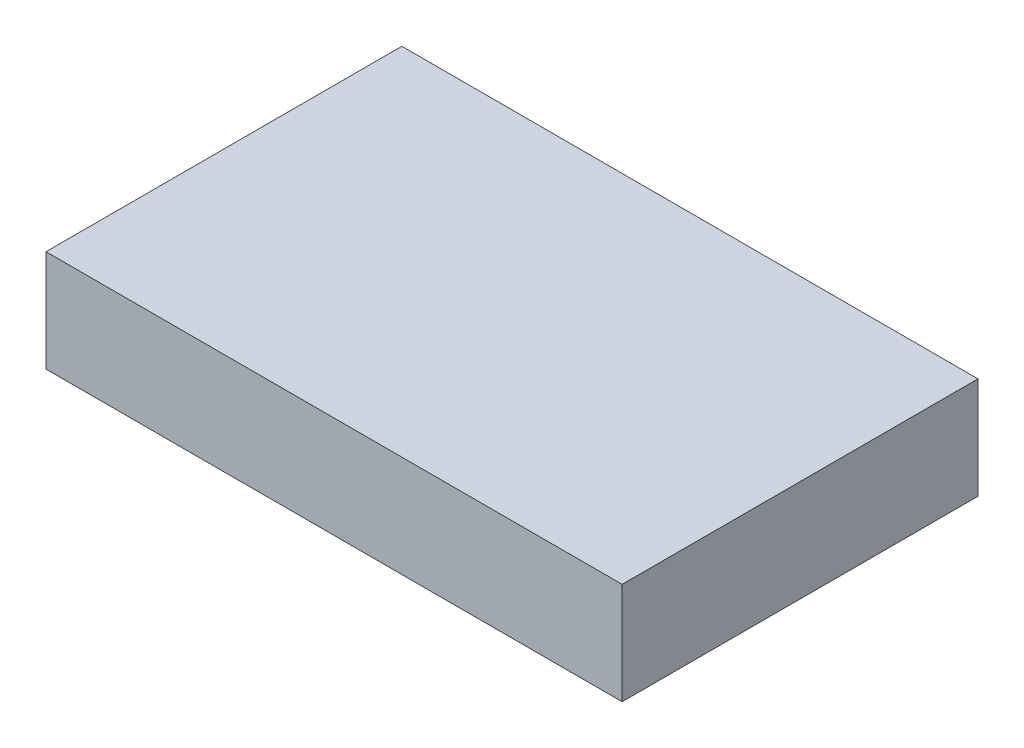
SolidWorks part; units mm, degrees
ref_plane "Front Plane" through (0, 0, 0) normal (0, 0, 1) x (1, 0, 0)
ref_plane "Top Plane" through (0, 0, 0) normal (0, 1, 0) x (1, 0, 0)
ref_plane "Right Plane" through (0, 0, 0) normal (1, 0, 0) x (0, 0, -1)
sketch "Sketch2" plane through (0, 0, 0) normal (0, 1, 0) x (1, 0, 0)
  line L1 (-17, -10.5) -> (17, -10.5)
  line L2 (-17, -10.5) -> (-17, 10.5)
  line L3 (-17, 10.5) -> (17, 10.5)
  line L4 (17, -10.5) -> (17, 10.5)
  line L5 (-17, -10.5) -> (17, 10.5) construction
  line L6 (-17, 10.5) -> (17, -10.5) construction
  point P0 (0, 0)
  dimension "D1" = 21
  dimension "D2" = 34
extrude "Boss-Extrude1" add sketch "Sketch2" along normal blind 6
